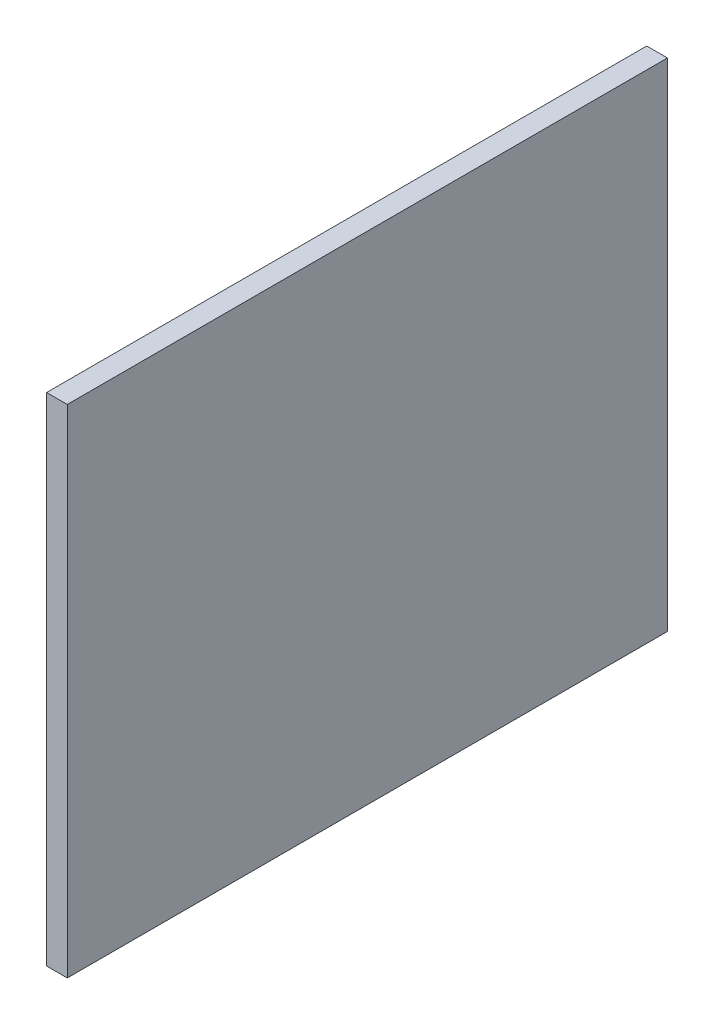
SolidWorks part; units mm, degrees
ref_plane "Front" through (0, 0, 0) normal (0, 0, 1) x (1, 0, 0)
ref_plane "Top" through (0, 0, 0) normal (0, 1, 0) x (1, 0, 0)
ref_plane "Right" through (0, 0, 0) normal (1, 0, 0) x (0, 0, -1)
sketch "Sketch1" plane through (0, 0, 0) normal (1, 0, 0) x (0, 0, -1)
  line L1 (-20.2867, 32.2129) -> (66.7133, 32.2129)
  line L2 (-20.2867, 32.2129) -> (-20.2867, -39.7871)
  line L3 (-20.2867, -39.7871) -> (66.7133, -39.7871)
  line L4 (66.7133, 32.2129) -> (66.7133, -39.7871)
  dimension "D1" = 72
  dimension "D2" = 87
extrude "Boss-Extrude1" add sketch "Sketch1" along normal blind 3
